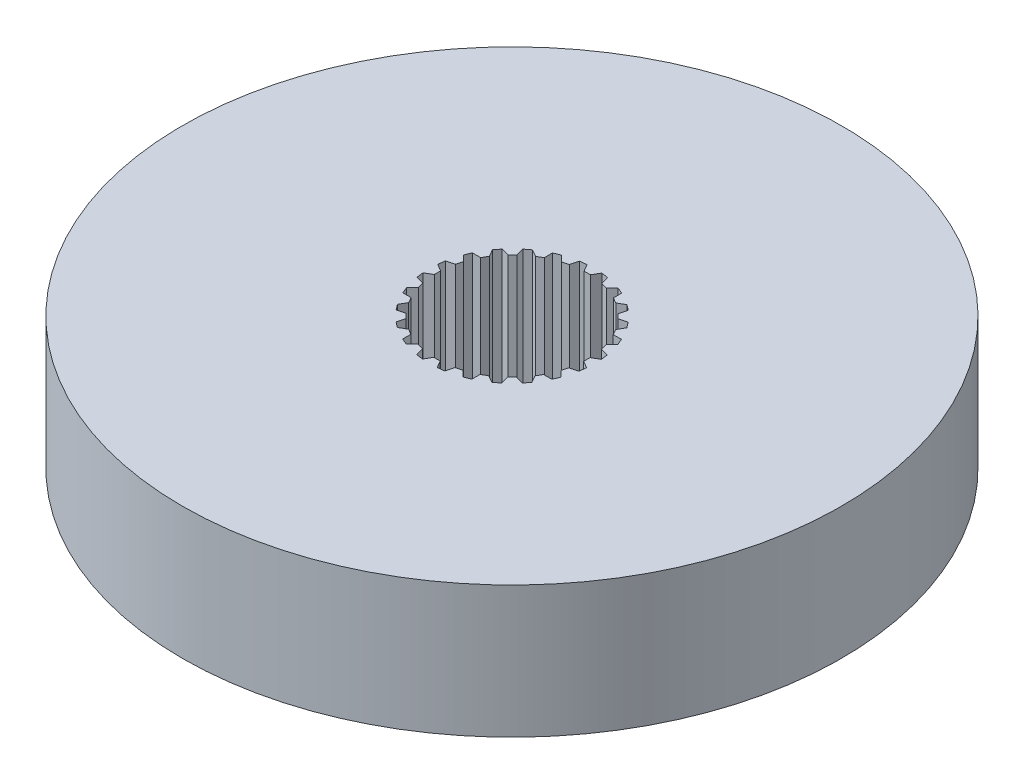
SolidWorks part; units mm, degrees
ref_plane "Front Plane" through (0, 0, 0) normal (0, 0, 1) x (1, 0, 0)
ref_plane "Top Plane" through (0, 0, 0) normal (0, 1, 0) x (1, 0, 0)
ref_plane "Right Plane" through (0, 0, 0) normal (1, 0, 0) x (0, 0, -1)
sketch "Sketch1" plane through (0, 0, 0) normal (0, 1, 0) x (1, 0, 0)
  line L0 (274.6284, 454.6081) -> (780.6456, 454.6081) construction
  circle A0 centre (0, 0) radius 23
  dimension "D1" = 46
sketch "Sketch5" plane through (0, 0, 0) normal (0, 1, 0) x (1, 0, 0)
  circle A0 centre (0, 0) radius 23
  circle A1 centre (0, 0) radius 25
  dimension "D1" = 46
  dimension "D2" = 50
sketch "Sketch6" plane through (0, 0, 0) normal (0, 1, 0) x (1, 0, 0)
  line L0 (-0.9689, -22.7363) -> (0.9689, -22.7363)
  line L1 (0.9689, -22.7363) -> (2.2189, -24.9013)
  line L2 (0, 33.3652) -> (0, -36.4848) construction
  line L3 (-0.9689, -22.7363) -> (-2.2189, -24.9013)
  line L4 (-4.9456, -22.1943) -> (-4.2985, -24.6091)
  line L5 (-6.8174, -21.6927) -> (-4.9456, -22.1943)
  line L6 (-6.8174, -21.6927) -> (-8.5852, -23.4605)
  line L7 (-10.5182, -22.6399) -> (-8.5852, -23.4605)
  line L8 (-10.5182, -20.1399) -> (-10.5182, -22.6399)
  line L9 (-12.1965, -19.171) -> (-10.5182, -20.1399)
  line L10 (-12.1965, -19.171) -> (-14.3615, -20.421)
  line L11 (-16.0164, -19.1281) -> (-14.3615, -20.421)
  line L12 (-15.3693, -16.7133) -> (-16.0164, -19.1281)
  line L13 (-16.7396, -15.343) -> (-15.3693, -16.7133)
  line L14 (-16.7396, -15.343) -> (-19.1544, -15.99)
  line L15 (-20.4182, -14.3129) -> (-19.1544, -15.99)
  line L16 (-19.1682, -12.1478) -> (-20.4182, -14.3129)
  line L17 (-20.1372, -10.4696) -> (-19.1682, -12.1478)
  line L18 (-20.1372, -10.4696) -> (-22.6372, -10.4696)
  line L19 (-23.4239, -8.5225) -> (-22.6372, -10.4696)
  line L20 (-21.6561, -6.7547) -> (-23.4239, -8.5225)
  line L21 (-22.1576, -4.8829) -> (-21.6561, -6.7547)
  line L22 (-22.1576, -4.8829) -> (-24.5725, -4.2358)
  line L23 (-24.8284, -2.1515) -> (-24.5725, -4.2358)
  line L24 (-22.6633, -0.9015) -> (-24.8284, -2.1515)
  line L25 (-22.6633, 1.0364) -> (-22.6633, -0.9015)
  line L26 (-22.6633, 1.0364) -> (-24.8284, 2.2864)
  line L27 (-24.5361, 4.366) -> (-24.8284, 2.2864)
  line L28 (-22.1213, 5.013) -> (-24.5361, 4.366)
  line L29 (-21.6197, 6.8849) -> (-22.1213, 5.013)
  line L30 (-21.6197, 6.8849) -> (-23.3875, 8.6526)
  line L31 (-22.567, 10.5857) -> (-23.3875, 8.6526)
  line L32 (-20.067, 10.5857) -> (-22.567, 10.5857)
  line L33 (-19.098, 12.2639) -> (-20.067, 10.5857)
  line L34 (-19.098, 12.2639) -> (-20.348, 14.429)
  line L35 (-19.0552, 16.0838) -> (-20.348, 14.429)
  line L36 (-16.6403, 15.4368) -> (-19.0552, 16.0838)
  line L37 (-15.27, 16.8071) -> (-16.6403, 15.4368)
  line L38 (-15.27, 16.8071) -> (-15.9171, 19.2219)
  line L39 (-14.24, 20.4857) -> (-15.9171, 19.2219)
  line L40 (-12.0749, 19.2357) -> (-14.24, 20.4857)
  line L41 (-10.3966, 20.2046) -> (-12.0749, 19.2357)
  line L42 (-10.3966, 20.2046) -> (-10.3966, 22.7046)
  line L43 (-8.4496, 23.4913) -> (-10.3966, 22.7046)
  line L44 (-6.6818, 21.7235) -> (-8.4496, 23.4913)
  line L45 (-4.8099, 22.2251) -> (-6.6818, 21.7235)
  line L46 (-4.8099, 22.2251) -> (-4.1629, 24.6399)
  line L47 (-2.0785, 24.8958) -> (-4.1629, 24.6399)
  line L48 (-0.8285, 22.7308) -> (-2.0785, 24.8958)
  line L49 (1.1093, 22.7308) -> (-0.8285, 22.7308)
  line L50 (1.1093, 22.7308) -> (2.3593, 24.8958)
  line L51 (4.4389, 24.6036) -> (2.3593, 24.8958)
  line L52 (5.086, 22.1888) -> (4.4389, 24.6036)
  line L53 (6.9578, 21.6872) -> (5.086, 22.1888)
  line L54 (6.9578, 21.6872) -> (8.7256, 23.455)
  line L55 (10.6586, 22.6344) -> (8.7256, 23.455)
  line L56 (10.6586, 20.1344) -> (10.6586, 22.6344)
  line L57 (12.3369, 19.1655) -> (10.6586, 20.1344)
  line L58 (12.3369, 19.1655) -> (14.5019, 20.4155)
  line L59 (16.1568, 19.1226) -> (14.5019, 20.4155)
  line L60 (15.5097, 16.7078) -> (16.1568, 19.1226)
  line L61 (16.88, 15.3375) -> (15.5097, 16.7078)
  line L62 (16.88, 15.3375) -> (19.2948, 15.9845)
  line L63 (20.5586, 14.3074) -> (19.2948, 15.9845)
  line L64 (19.3086, 12.1424) -> (20.5586, 14.3074)
  line L65 (20.2776, 10.4641) -> (19.3086, 12.1424)
  line L66 (20.2776, 10.4641) -> (22.7776, 10.4641)
  line L67 (23.5643, 8.517) -> (22.7776, 10.4641)
  line L68 (21.7965, 6.7492) -> (23.5643, 8.517)
  line L69 (22.298, 4.8774) -> (21.7965, 6.7492)
  line L70 (22.298, 4.8774) -> (24.7129, 4.2303)
  line L71 (24.9688, 2.146) -> (24.7129, 4.2303)
  line L72 (22.8037, 0.896) -> (24.9688, 2.146)
  line L73 (22.8037, -1.0419) -> (22.8037, 0.896)
  line L74 (22.8037, -1.0419) -> (24.9688, -2.2919)
  line L75 (24.6765, -4.3714) -> (24.9688, -2.2919)
  line L76 (22.2617, -5.0185) -> (24.6765, -4.3714)
  line L77 (21.7601, -6.8903) -> (22.2617, -5.0185)
  line L78 (21.7601, -6.8903) -> (23.5279, -8.6581)
  line L79 (22.7074, -10.5912) -> (23.5279, -8.6581)
  line L80 (20.2074, -10.5912) -> (22.7074, -10.5912)
  line L81 (19.2384, -12.2694) -> (20.2074, -10.5912)
  line L82 (19.2384, -12.2694) -> (20.4884, -14.4345)
  line L83 (19.1955, -16.0893) -> (20.4884, -14.4345)
  line L84 (16.7807, -15.4423) -> (19.1955, -16.0893)
  line L85 (15.4104, -16.8126) -> (16.7807, -15.4423)
  line L86 (15.4104, -16.8126) -> (16.0575, -19.2274)
  line L87 (14.3804, -20.4912) -> (16.0575, -19.2274)
  line L88 (12.2153, -19.2412) -> (14.3804, -20.4912)
  line L89 (10.537, -20.2101) -> (12.2153, -19.2412)
  line L90 (10.537, -20.2101) -> (10.537, -22.7101)
  line L91 (8.59, -23.4968) -> (10.537, -22.7101)
  line L92 (6.8222, -21.729) -> (8.59, -23.4968)
  line L93 (4.9503, -22.2306) -> (6.8222, -21.729)
  line L94 (4.9503, -22.2306) -> (4.3033, -24.6454)
  line L95 (2.2189, -24.9013) -> (4.3033, -24.6454)
  line L96 (-4.2985, -24.6091) -> (-2.2189, -24.9013)
  circle A0 centre (0, 0) radius 23 construction
  circle A1 centre (0, 0) radius 25 construction
  point P11 (0, -23)
  point P131 (0.0702, -0.0027)
  dimension "D4" = 2.5
  dimension "D1" = 2.1
  dimension "D5" = 112
  dimension "D6" = 120
  dimension "D2" = 1.9379
  dimension "D3" = 24
sketch "Sketch8" plane through (0, 0, 0) normal (0, 1, 0) x (1, 0, 0)
  circle A0 centre (0, 0) radius 100
  dimension "D1" = 200
extrude "Boss-Extrude4" add sketch "Sketch8" along normal blind 40 contours A0
extrude "Cut-Extrude1" cut sketch "Sketch6" along normal through all
